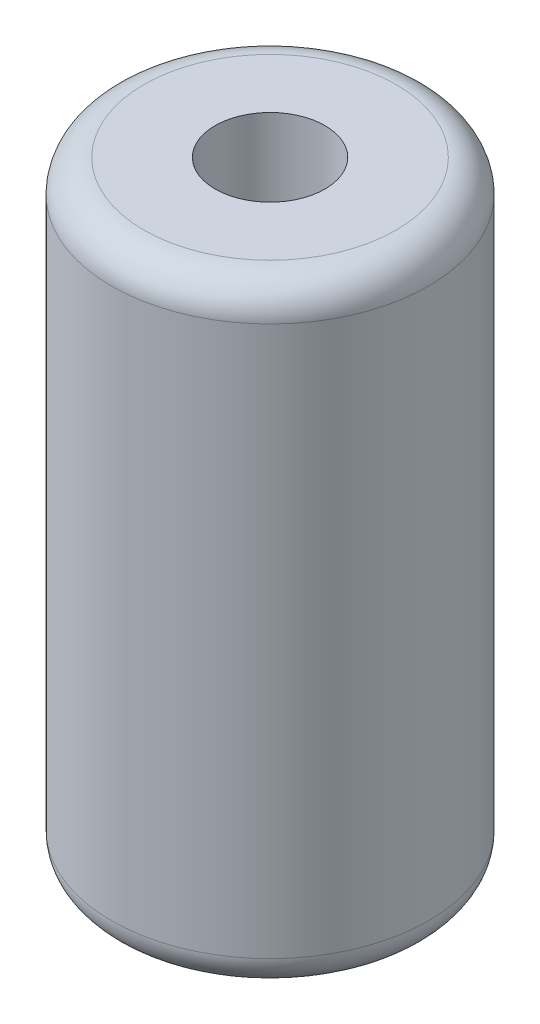
SolidWorks part; units mm, degrees
ref_plane "前视基准面" through (0, 0, 0) normal (0, 0, 1) x (1, 0, 0)
ref_plane "上视基准面" through (0, 0, 0) normal (0, 1, 0) x (1, 0, 0)
ref_plane "右视基准面" through (0, 0, 0) normal (1, 0, 0) x (0, 0, -1)
sketch "草图1" plane through (0, 0, 0) normal (0, 1, 0) x (1, 0, 0)
  circle A0 centre (0, 0) radius 4.9
  circle A1 centre (0, 0) radius 1.7
  dimension "D1" = 9.8
  dimension "D2" = 3.4
extrude "凸台-拉伸1" add sketch "草图1" along normal blind 19
fillet "圆角1" radius 1 2 edges at (0, 0, 4.9) (0, 19, 4.9)
